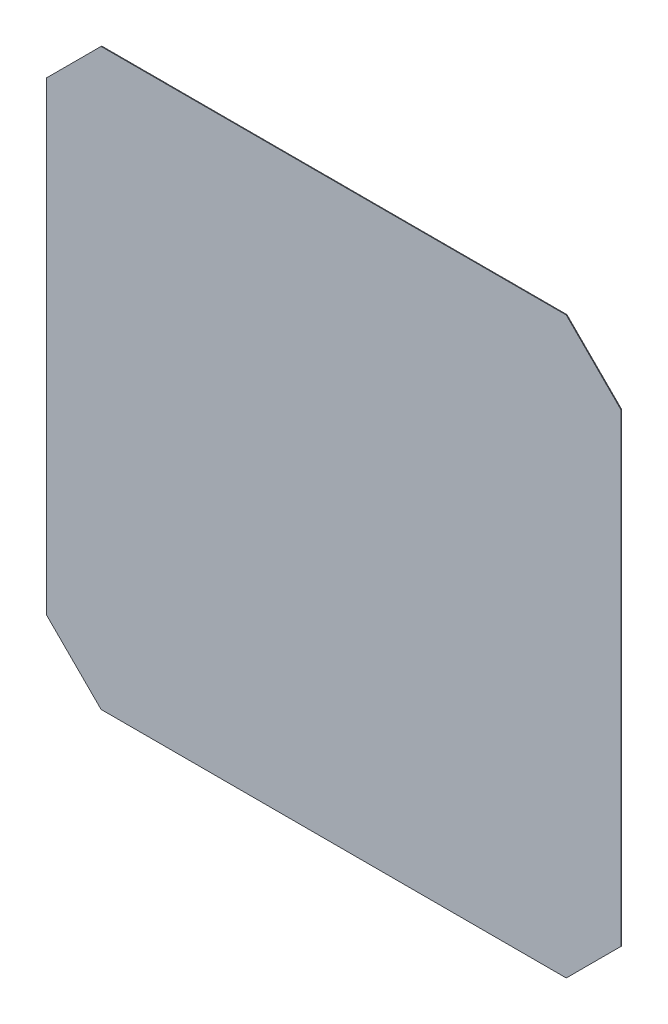
SolidWorks part; units mm, degrees
ref_plane "Front Plane" through (0, 0, 0) normal (0, 0, 1) x (1, 0, 0)
ref_plane "Top Plane" through (0, 0, 0) normal (0, 1, 0) x (1, 0, 0)
ref_plane "Right Plane" through (0, 0, 0) normal (1, 0, 0) x (0, 0, -1)
sketch "Sketch1" plane through (0, 0, 0) normal (0, 0, 1) x (1, 0, 0)
  line L0 (0, -62.5) -> (0, 62.5) construction
  line L1 (-62.5, 0) -> (62.5, 0) construction
  line L3 (-62.5, -62.5) -> (62.5, -62.5)
  line L4 (-62.5, -62.5) -> (-62.5, 62.5)
  line L5 (-62.5, 62.5) -> (62.5, 62.5)
  line L6 (62.5, -62.5) -> (62.5, 62.5)
  line L7 (-62.5, -62.5) -> (62.5, 62.5) construction
  line L8 (-62.5, 62.5) -> (62.5, -62.5) construction
  point P0 (0, 0)
  point P4 (0, 0)
  point P8 (0, 0)
  point P13 (0, 0)
  point P14 (0, 0)
  dimension "D1" = 125
extrude "Boss-Extrude1" add sketch "Sketch1" along normal blind 0.15
sketch "Sketch2" plane through (0, 0, 0.15) normal (0, 0, 1) x (1, 0, 0)
  line L0 (56.5685, -56.5685) -> (-56.5685, 56.5685) construction
  line L1 (-62.5, 50.6371) -> (-50.6371, 62.5)
  line L2 (62.5, 62.5) -> (-62.5, 62.5) construction
  line L3 (-62.5, 50.6371) -> (-62.5, 62.5)
  line L4 (-62.5, 62.5) -> (-50.6371, 62.5)
  point P4 (0, 0)
  point P9 (-56.5685, 56.5685)
  dimension "D1" = 160
extrude "Cut-Extrude1" cut sketch "Sketch2" against normal through all
mirror "Mirror1" about plane through (0, 0, 0) normal (0, 1, 0) of "Cut-Extrude1"
mirror "Mirror2" about plane through (0, 0, 0) normal (1, 0, 0) of "Mirror1", "Cut-Extrude1"
sketch "Sketch4" plane through (0, 0, 0) normal (0, 0, -1) x (-1, 0, 0)
  line L0 (0, 0) -> (0, 62.5) construction
  line L1 (-50.6371, 62.5) -> (50.6371, 62.5) construction
  line L3 (-1.5, 57.1) -> (1.5, 57.1)
  line L4 (-1.5, 57.1) -> (-1.5, 62.5)
  line L5 (-1.5, 62.5) -> (1.5, 62.5)
  line L6 (1.5, 57.1) -> (1.5, 62.5)
  line L7 (-1.5, 57.1) -> (1.5, 62.5) construction
  line L8 (-1.5, 62.5) -> (1.5, 57.1) construction
  point P7 (0, 59.8)
  dimension "D1" = 5.4
  dimension "D2" = 3
extrude "Boss-Extrude2" add sketch "Sketch4" along normal blind 0.01
pattern_linear "LPattern1" count 2 spacing 38.5 along (-1, 0, 0) count 2 spacing 38.5 along (1, 0, 0) of "Boss-Extrude2"
mirror "Mirror3" about plane through (0, 0, 0) normal (0, 1, 0) of "LPattern1", "Boss-Extrude2"
